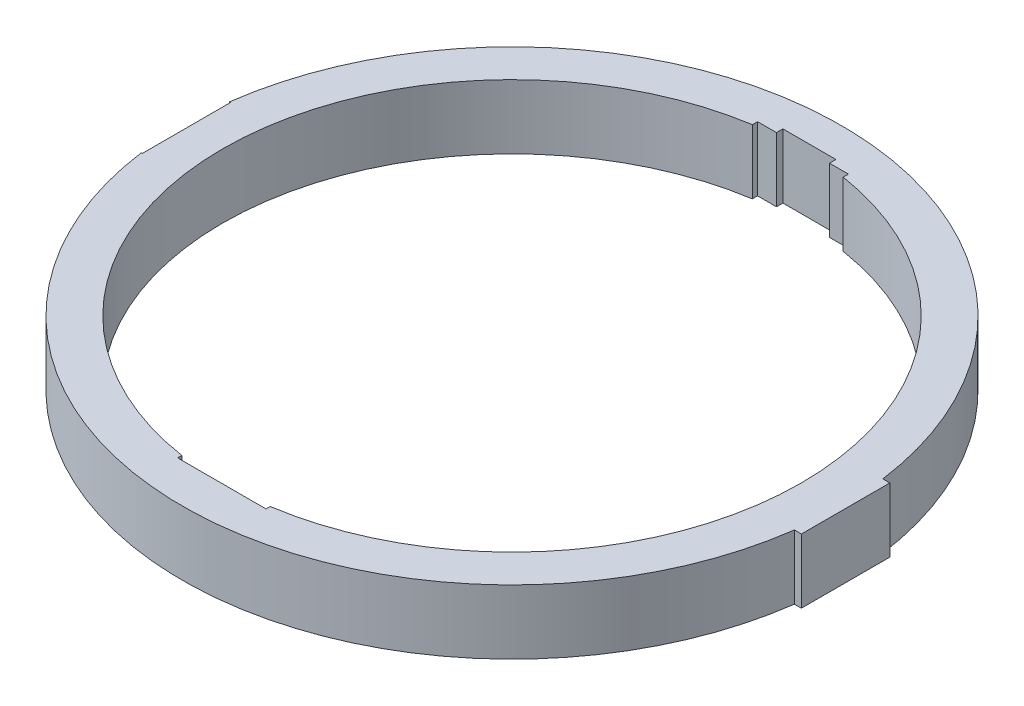
SolidWorks part; units mm, degrees
ref_plane "Front Plane" through (0, 0, 0) normal (0, 0, 1) x (1, 0, 0)
ref_plane "Top Plane" through (0, 0, 0) normal (0, 1, 0) x (1, 0, 0)
ref_plane "Right Plane" through (0, 0, 0) normal (1, 0, 0) x (0, 0, -1)
sketch "Sketch1" plane through (0, 0, 0) normal (0, 1, 0) x (1, 0, 0)
  circle A0 centre (0, 0) radius 360
  circle A1 centre (0, 0) radius 410
  dimension "D1" = 720
  dimension "D2" = 820
extrude "Boss-Extrude1" add sketch "Sketch1" along normal blind 80
sketch "Sketch3" plane through (0, 80, 0) normal (0, 1, 0) x (1, 0, 0)
  line L0 (-56.5, 287.0264) -> (56.5, 287.0264)
  line L1 (56.5, 287.0264) -> (56.5, 362)
  line L2 (56.5, 362) -> (33, 362)
  line L3 (33, 362) -> (33, 370)
  line L4 (33, 370) -> (-33, 370)
  line L5 (-33, 370) -> (-33, 362)
  line L6 (-33, 362) -> (-56.5, 362)
  line L7 (-56.5, 362) -> (-56.5, 287.0264)
  line L8 (0, 0) -> (0, 410) construction
  circle A0 centre (0, 0) radius 410 construction
  circle A1 centre (0, 0) radius 360 construction
  point P3 (0, 287.0264)
  point P16 (0, 360)
  dimension "D1" = 8
  dimension "D2" = 66
  dimension "D3" = 113
  dimension "D4" = 74.9736
  dimension "D5" = 10
extrude "Cut-Extrude2" cut sketch "Sketch3" against normal through all both and the other way through all
ref_plane "Plane1" through (0, 0, 361) normal (0, 0, 1) x (1, 0, 0)
sketch "Sketch5" plane through (0, 0, 361) normal (0, 0, 1) x (1, 0, 0)
  line L0 (-55, 0) -> (55, 0)
  line L1 (-410, 0) -> (410, 0) construction
  line L2 (55, 0) -> (55, 80)
  line L3 (360, 80) -> (-360, 80) construction
  line L4 (55, 80) -> (-55, 80)
  line L5 (-55, 80) -> (-55, 0)
  point P6 (0, 0)
  dimension "D1" = 110
extrude "Cut-Extrude3" cut sketch "Sketch5" against normal blind 30
sketch "Sketch6" plane through (0, 0, 361) normal (0, 0, -1) x (-1, 0, 0)
  line L0 (0, 80) -> (0, 0) construction
  line L1 (-55, 80) -> (55, 80) construction
  line L2 (55, 0) -> (-55, 0) construction
  circle A0 centre (0, 40) radius 31
  dimension "D1" = 62
extrude "Cut-Extrude4" cut sketch "Sketch6" against normal blind 12
ref_plane "Plane2" through (415, 0, 0) normal (1, 0, 0) x (0, 0, -1)
sketch "Sketch7" plane through (415, 0, 0) normal (1, 0, 0) x (0, 0, -1)
  line L0 (-55, 0) -> (55, 0)
  line L1 (-410, 0) -> (410, 0) construction
  line L2 (55, 0) -> (55, 80)
  line L3 (410, 80) -> (-410, 80) construction
  line L4 (55, 80) -> (-55, 80)
  line L5 (355.5387, 80) -> (-355.7738, 80) construction
  line L6 (-55, 80) -> (-55, 0)
  point P5 (0, 0)
  dimension "D1" = 110
extrude "Boss-Extrude2" add sketch "Sketch7" against normal up to surface (8.7058 mm away)
ref_plane "Plane3" through (-405, 0, 0) normal (1, 0, 0) x (0, 0, -1)
sketch "Sketch9" plane through (-405, 0, 0) normal (1, 0, 0) x (0, 0, -1)
  line L4 (55, 0) -> (55, 80)
  line L5 (55, 80) -> (-55, 80)
  line L6 (-55, 80) -> (-55, 0)
  line L7 (-55, 0) -> (55, 0)
  line L8 (55, 0) -> (55, 80)
  line L9 (55, 80) -> (-55, 80)
  line L10 (-55, 80) -> (-55, 0)
  line L11 (-55, 0) -> (55, 0)
  dimension "D1" = 0
extrude "Cut-Extrude5" cut sketch "Sketch9" against normal blind 41.7
sketch "Sketch10" plane through (-405, 0, 0) normal (-1, 0, 0) x (0, 0, 1)
  line L0 (0, 80) -> (0, 0) construction
  line L1 (-55, 80) -> (55, 80) construction
  line L2 (55, 0) -> (-55, 0) construction
  circle A0 centre (0, 40) radius 31
  dimension "D1" = 62
extrude "Cut-Extrude6" cut sketch "Sketch10" against normal blind 12
ref_plane "Plane4" through (0, 40, 0) normal (0, 1, 0) x (1, 0, 0)
sketch "Sketch11" plane through (0, 40, 0) normal (0, 1, 0) x (1, 0, 0)
  line L0 (-405, 0) -> (415, 0) construction
  line L1 (-405, 55) -> (-405, -55) construction
  line L2 (415, 55) -> (415, -55) construction
sketch "Sketch12" plane through (0, 0, -370) normal (0, 0, 1) x (1, 0, 0)
  line L0 (0, 80) -> (0, 0) construction
  line L1 (33, 80) -> (-33, 80) construction
  line L2 (33, 0) -> (-33, 0) construction
  circle A0 centre (0, 40) radius 16.5
  dimension "D1" = 33
